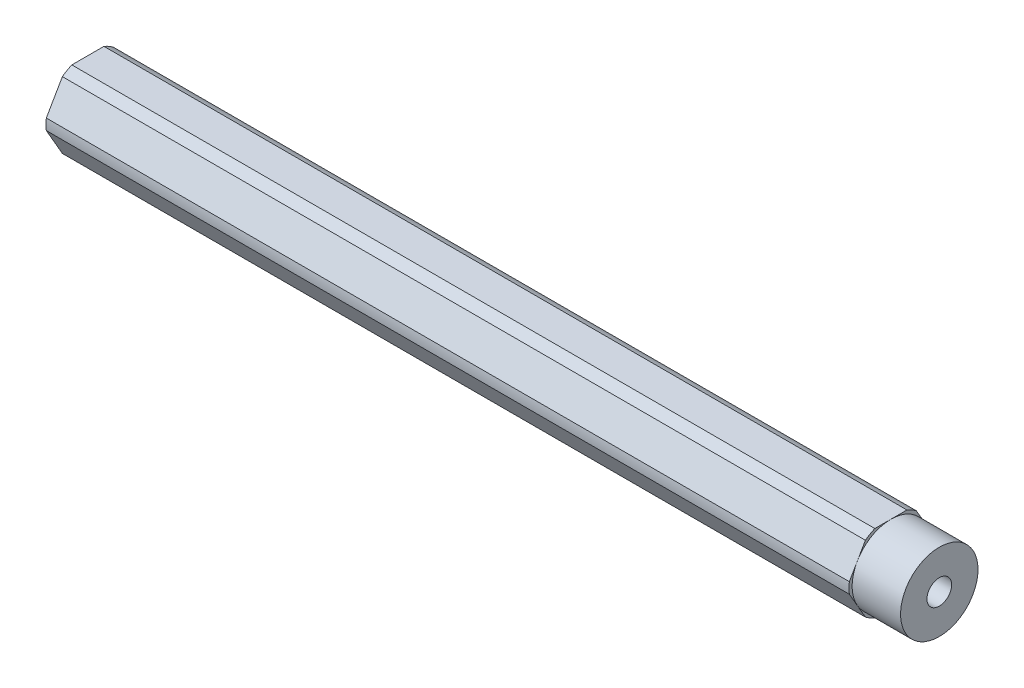
SolidWorks part; units mm, degrees
material "7075-T6 (SN)"
ref_plane "Front Plane" through (0, 0, 0) normal (0, 0, 1) x (1, 0, 0)
ref_plane "Top Plane" through (0, 0, 0) normal (0, 1, 0) x (1, 0, 0)
ref_plane "Right Plane" through (0, 0, 0) normal (1, 0, 0) x (0, 0, -1)
sketch "Sketch1" plane through (0, 0, 0) normal (1, 0, 0) x (0, 0, -1)
  line L1 (3.6662, 6.35) -> (-3.6662, 6.35)
  line L2 (-3.6662, 6.35) -> (-7.3323, 0)
  line L3 (-7.3323, 0) -> (-3.6662, -6.35)
  line L4 (-3.6662, -6.35) -> (3.6662, -6.35)
  line L5 (3.6662, -6.35) -> (7.3323, 0)
  line L6 (7.3323, 0) -> (3.6662, 6.35)
  circle A0 centre (0, 0) radius 6.875
  circle A1 centre (0, 0) radius 2.0193
  circle A2 centre (0, 0) radius 6.35 construction
  dimension "D1" = 12.7
  dimension "D2" = 13.75
  dimension "D3" = 4.0386
extrude "Boss-Extrude1" add sketch "Sketch1" along normal mid plane 139.6492 contours L6 A0 L1 L2 L3 L4 L5 A1
hole_wizard "#10-32 Tapped Hole1" positions "3DSketch1" profile "Sketch2" tap size "#10-32" standard "ANSI Inch"
sketch3d "3DSketch1"
  circle A0 centre (-69.8246, 0, 0) radius 2.0193 construction
  circle A1 centre (69.8246, 0, 0) radius 2.0193 construction
  point P0 (69.8246, 0, 0)
  point P2 (-69.8246, 0, 0)
  point P7 (-67.8053, 0, 0)
  point P10 (71.8439, 0, 0)
sketch "Sketch2" plane through (69.8246, 0, 0) normal (0, 1, 0) x (0, 0, -1)
  line L0 (0, 0) -> (0, 17.5608)
  line L1 (0, 17.5608) -> (2.0193, 16.3474)
  line L2 (2.0193, 16.3474) -> (2.0193, 0)
  line L5 (2.0193, 0) -> (0, 0)
  line L10 (0, 17.5608) -> (-2.0193, 16.3474) construction
  line L11 (0, -6.35) -> (0, 107.95) construction
  dimension "Tap Drill Dia." = 4.0386
  dimension "Tap Drill Depth" = 16.3474
  dimension "Drill Angle" = 118
cosmetic thread "Hole Thread1" parameters "D1"=13.97, "D2"=4.826
cosmetic thread "Hole Thread2" parameters "D1"=13.97, "D2"=4.826
sketch "Sketch3" plane through (69.8246, 0, 0) normal (1, 0, 0) x (0, 0, -1)
  circle A0 centre (0, 0) radius 6.35
  dimension "D1" = 12.7
extrude "Cut-Extrude-Thin1" cut sketch "Sketch3" against normal blind 7.9375 thin
equation "\"D2@Sketch1\"=13.75mm"
